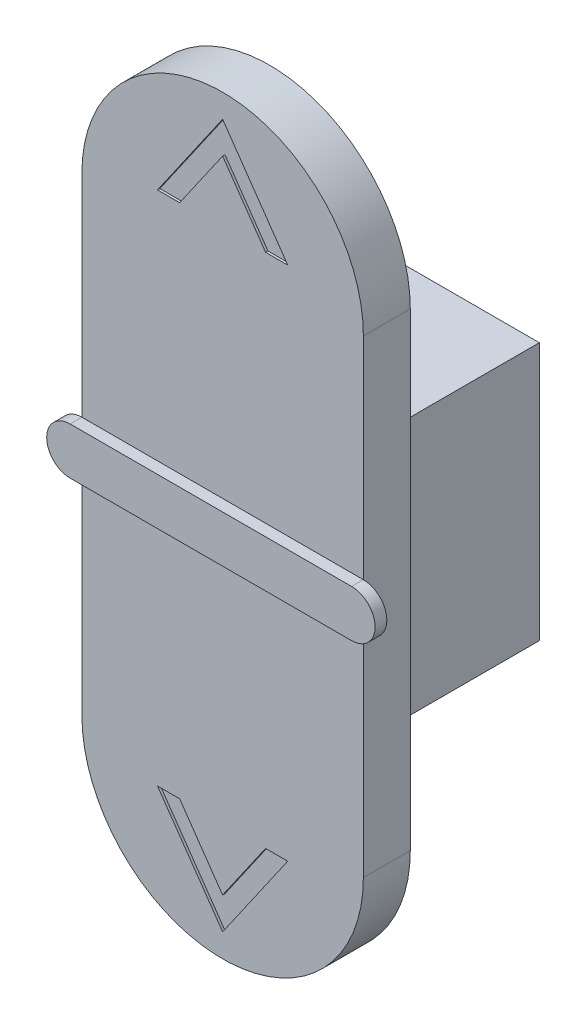
SolidWorks part; units mm, degrees
material "ABS"
ref_plane "Front Plane" through (0, 0, 0) normal (0, 0, 1) x (1, 0, 0)
ref_plane "Top Plane" through (0, 0, 0) normal (0, 1, 0) x (1, 0, 0)
ref_plane "Right Plane" through (0, 0, 0) normal (1, 0, 0) x (0, 0, -1)
sketch "Sketch1" plane through (0, 0, 0) normal (0, 0, 1) x (1, 0, 0)
  line L0 (0, 10) -> (0, -10) construction
  line L1 (6, 10) -> (6, -10)
  line L2 (-6, 10) -> (-6, -10)
  arc A0 (6, 10) -> (-6, 10) centre (0, 10) ccw
  arc A1 (-6, -10) -> (6, -10) centre (0, -10) ccw
  point P3 (0, 0)
  dimension "D1" = 12
  dimension "D2" = 20
extrude "Boss-Extrude1" add sketch "Sketch1" along normal blind 2
sketch "Sketch2" plane through (0, 0, 2) normal (0, 0, 1) x (1, 0, 0)
  line L5 (-6, 0) -> (6, 0) construction
  line L10 (-6, 1) -> (6, 1)
  line L11 (-6, -1) -> (6, -1)
  arc A0 (-6, 1) -> (-6, -1) centre (-6, 0) ccw
  arc A1 (6, -1) -> (6, 1) centre (6, 0) ccw
  point P2 (0, 0)
  dimension "D1" = 12
  dimension "D2" = 2
extrude "Boss-Extrude2" add sketch "Sketch2" along normal blind 0.5
sketch "Sketch3" plane through (0, 0, 2) normal (0, 0, 1) x (1, 0, 0)
  line L0 (0, 15) -> (-2.7756, 11.0031)
  line L1 (-2.7756, 11.0031) -> (-1.8319, 11.0031)
  line L2 (-1.8319, 11.0031) -> (0, 13.6411)
  line L3 (0, 23.2959) -> (0, 0) construction
  line L4 (-12.0086, 0) -> (10.6615, 0) construction
  line L5 (0, 15) -> (2.7756, 11.0031)
  line L6 (1.8319, 11.0031) -> (0, 13.6411)
  line L7 (2.7756, 11.0031) -> (1.8319, 11.0031)
  line L8 (-2.7756, -11.0031) -> (-1.8319, -11.0031)
  line L9 (0, -15) -> (-2.7756, -11.0031)
  line L10 (2.7756, -11.0031) -> (1.8319, -11.0031)
  line L11 (1.8319, -11.0031) -> (0, -13.6411)
  line L12 (0, -15) -> (2.7756, -11.0031)
  line L13 (-1.8319, -11.0031) -> (0, -13.6411)
  dimension "D1" = 0.9437
  dimension "D2" = 3.9969
  dimension "D3" = 3.2116
  dimension "D4" = 15
extrude "Cut-Extrude1" cut sketch "Sketch3" against normal blind 0.1
sketch "Sketch4" plane through (0, 0, 0) normal (0, 0, -1) x (-1, 0, 0)
  line L1 (-4.5, -4.5) -> (4.5, -4.5)
  line L2 (-4.5, -4.5) -> (-4.5, 4.5)
  line L3 (-4.5, 4.5) -> (4.5, 4.5)
  line L4 (4.5, -4.5) -> (4.5, 4.5)
  line L5 (-4.5, -4.5) -> (4.5, 4.5) construction
  line L6 (-4.5, 4.5) -> (4.5, -4.5) construction
  point P0 (0, 0)
  dimension "D1" = 9
  dimension "D2" = 9
extrude "Extrude-Thin1" add sketch "Sketch4" along normal blind 6 thin
